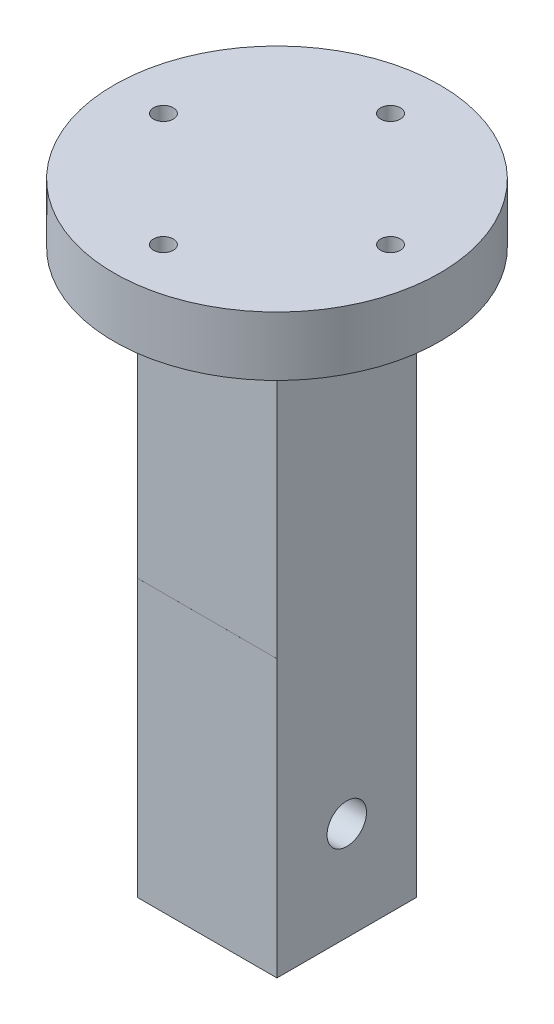
SolidWorks part; units mm, degrees
ref_plane "Front Plane" through (0, 0, 0) normal (0, 0, 1) x (1, 0, 0)
ref_plane "Top Plane" through (0, 0, 0) normal (0, 1, 0) x (1, 0, 0)
ref_plane "Right Plane" through (0, 0, 0) normal (1, 0, 0) x (0, 0, -1)
sketch "Sketch1" plane through (0, 0, 0) normal (0, 1, 0) x (1, 0, 0)
  line L1 (-4.4907, 4.4895) -> (4.4907, 4.4895)
  line L2 (-4.4907, 4.4895) -> (-4.4907, -4.4895)
  line L3 (-4.4907, -4.4895) -> (4.4907, -4.4895)
  line L4 (4.4907, 4.4895) -> (4.4907, -4.4895)
  line L5 (-4.4907, 4.4895) -> (4.4907, -4.4895) construction
  line L6 (-4.4907, -4.4895) -> (4.4907, 4.4895) construction
  point P0 (0, 0)
  dimension "D1" = 12.7
  dimension "D2" = 8.9814
extrude "Boss-Extrude1" add sketch "Sketch1" along normal blind 18.415
sketch "Sketch2" plane through (0, 18.415, 0) normal (0, 1, 0) x (1, 0, 0)
  circle A0 centre (0, 0) radius 10.4775
  dimension "D1" = 20.955
extrude "Boss-Extrude2" add sketch "Sketch2" along normal blind 3.81
sketch "Sketch4" plane through (0, 0, 0) normal (0, -1, 0) x (1, 0, 0)
  circle A0 centre (0, 0) radius 10.4775
  dimension "D1" = 20.955
extrude "Boss-Extrude4" add sketch "Sketch4" along normal blind 5.08
sketch "Sketch5" plane through (0, -5.08, 0) normal (0, -1, 0) x (1, 0, 0)
  line L0 (0, 10.4544) -> (0, 13.6172) construction
  line L2 (2.1788, 5.6311) -> (2.1687, 5.6844)
  line L3 (0, 17.1951) -> (-1.8362, 7.4496)
  line L4 (-1.27, 10.4544) -> (1.27, 10.4544) construction
  line L5 (2.1484, 5.6311) -> (2.1788, 5.6311)
  line L6 (2.0215, 5.2986) -> (2.1687, 5.6844) construction
  line L7 (5.0878, 5.743) -> (7.9909, 15.2255)
  line L8 (7.9909, 15.2255) -> (1.8362, 7.4496)
  line L10 (7.1739, 2.7207) -> (14.1513, 9.7679)
  line L11 (14.1513, 9.7679) -> (5.0878, 5.743)
  line L13 (7.6166, -0.9248) -> (17.0697, 2.0726)
  line L14 (17.0697, 2.0726) -> (7.1739, 2.7207)
  line L16 (6.3143, -4.3585) -> (16.0777, -6.0975)
  line L17 (16.0777, -6.0975) -> (7.6166, -0.9248)
  line L19 (3.5656, -6.7937) -> (11.4024, -12.8707)
  line L20 (11.4024, -12.8707) -> (6.3143, -4.3585)
  line L22 (0, -7.6725) -> (4.1151, -16.6954)
  line L23 (4.1151, -16.6954) -> (3.5656, -6.7937)
  line L25 (-3.5656, -6.7937) -> (-4.1151, -16.6954)
  line L26 (-4.1151, -16.6954) -> (0, -7.6725)
  line L28 (-6.3143, -4.3585) -> (-11.4024, -12.8707)
  line L29 (-11.4024, -12.8707) -> (-3.5656, -6.7937)
  line L31 (-7.6166, -0.9248) -> (-16.0777, -6.0975)
  line L32 (-16.0777, -6.0975) -> (-6.3143, -4.3585)
  line L34 (-7.1739, 2.7207) -> (-17.0697, 2.0726)
  line L35 (-17.0697, 2.0726) -> (-7.6166, -0.9248)
  line L37 (-5.0878, 5.743) -> (-14.1513, 9.7679)
  line L38 (-14.1513, 9.7679) -> (-7.1739, 2.7207)
  line L40 (-1.8362, 7.4496) -> (-7.9909, 15.2255)
  line L41 (-7.9909, 15.2255) -> (-5.0878, 5.743)
  line L43 (3.7783, 9.9032) -> (6.7902, 17.7977) construction
  line L44 (1.8362, 7.4496) -> (0, 17.1951)
  line L46 (-3.8459, 4.3411) -> (-3.3966, 4.9919) [skipped]
  line L47 (-1.3879, 5.6311) -> (-0.6877, 5.9986) [skipped]
  line L49 (0.6877, 5.9986) -> (1.3879, 5.6311) [skipped]
  line L51 (5.4227, 2.0566) -> (5.872, 1.4057) [skipped]
  line L52 (5.3274, 2.8416) -> (5.4227, 2.0566) [skipped]
  line L53 (-4.773, -3.2946) -> (-5.7573, -0.6991) [skipped]
  line L54 (-5.8526, -1.4841) -> (-5.7573, -0.6991) [skipped]
  line L55 (-2.1033, -5.6597) -> (-2.6952, -5.1353) [skipped]
  line L56 (0.7679, -5.9889) -> (0, -5.7996) [skipped]
  line L57 (3.4631, -4.946) -> (2.6952, -5.1353) [skipped]
  line L58 (5.7573, -0.6991) -> (4.773, -3.2946) [skipped]
  line L59 (5.3649, -2.7701) -> (4.773, -3.2946) [skipped]
  circle A0 centre (0, 0) radius 20.0803
  point P49 (0, 0)
  circle M1 centre (0, 0) radius 10.4775
  dimension "D1" = 10.67
  dimension "D2" = 10.67
  dimension "D3" = 2.54
  dimension "D4" = 2.54
  dimension "D5" = 13
extrude "Cut-Extrude1" cut sketch "Sketch5" against normal blind 5.08 contours A0 L44 L8 L7 L11 L10 L14 L13 L17 L16 L20 L19 L23 L22 L26 L25 L29 L28 L32 L31 L35 L34 L38 L37 L41 L40 L3 M1 | L41 L37 M1 | L40 L3 M1 | L44 L8 M1 | L11 L7 M1 | L14 L10 M1 | L17 L13 M1 | L20 L16 M1 | L23 L19 M1 | L26 L22 M1 | L29 L25 M1 | L32 L28 M1 | L35 L31 M1 | L38 L34 M1
sketch "Sketch6" plane through (0, -5.08, 0) normal (0, -1, 0) x (1, 0, 0)
  circle A0 centre (0, 0) radius 11.7475
  dimension "D1" = 23.495
extrude "Boss-Extrude5" add sketch "Sketch6" along normal blind 1.27
sketch "Sketch10" plane through (0, 22.225, 0) normal (0, 1, 0) x (1, 0, 0)
  circle A0 centre (0, 7.3025) radius 0.635
  circle A1 centre (7.3025, 0) radius 0.635
  circle A2 centre (-7.3025, 0) radius 0.635
  circle A3 centre (0, -7.3025) radius 0.635
  dimension "D1" = 1.27
  dimension "D2" = 7.3025
  dimension "D4" = 7.3025
  dimension "D3" = 7.3025
  dimension "D5" = 7.3025
extrude "Cut-Extrude3" cut sketch "Sketch10" against normal blind 5.08
sketch "Sketch11" plane through (0, -6.35, 0) normal (0, -1, 0) x (1, 0, 0)
  line L1 (-4.4901, 4.4901) -> (4.4901, 4.4901)
  line L2 (-4.4901, 4.4901) -> (-4.4901, -4.4901)
  line L3 (-4.4901, -4.4901) -> (4.4901, -4.4901)
  line L4 (4.4901, 4.4901) -> (4.4901, -4.4901)
  line L5 (-4.4901, 4.4901) -> (4.4901, -4.4901) construction
  line L6 (-4.4901, -4.4901) -> (4.4901, 4.4901) construction
  point P0 (0, 0)
  dimension "D1" = 12.7
extrude "Boss-Extrude6" add sketch "Sketch11" along normal blind 11.43
sketch "Sketch12" plane through (4.4901, 0, 0) normal (1, 0, 0) x (0, 0, -1)
  line L0 (4.4901, -17.78) -> (-4.4901, -17.78) construction
  circle A0 centre (0, -11.43) radius 1.27
  dimension "D1" = 2.54
  dimension "D2" = 6.35
extrude "Cut-Extrude4" cut sketch "Sketch12" against normal through all
sketch "Sketch13" plane through (0, -6.35, 0) normal (0, -1, 0) x (1, 0, 0)
  line L1 (-4.4901, 4.4901) -> (4.4901, 4.4901)
  line L2 (-4.4901, 4.4901) -> (-4.4901, -4.4901)
  line L3 (-4.4901, -4.4901) -> (4.4901, -4.4901)
  line L4 (4.4901, 4.4901) -> (4.4901, -4.4901)
  circle A0 centre (0, 0) radius 16.3326
extrude "Cut-Extrude5" cut sketch "Sketch13" against normal up to surface (24.765 mm away) up to face at (0, 18.415, -6.6675)
